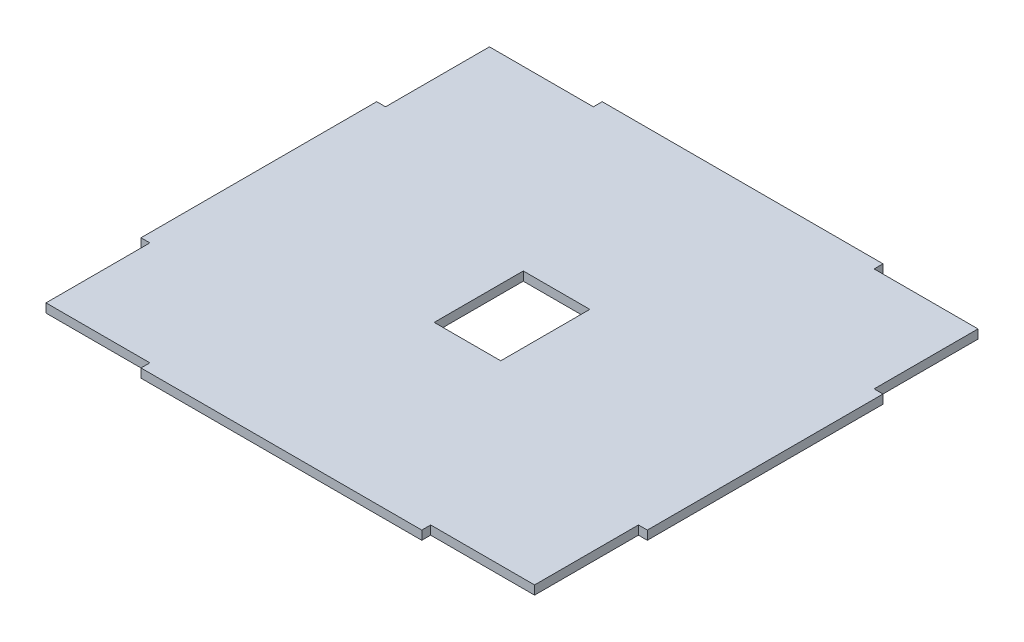
SolidWorks part; units mm, degrees
ref_plane "Front Plane" through (0, 0, 0) normal (0, 0, 1) x (1, 0, 0)
ref_plane "Top Plane" through (0, 0, 0) normal (0, 1, 0) x (1, 0, 0)
ref_plane "Right Plane" through (0, 0, 0) normal (1, 0, 0) x (0, 0, -1)
sketch "Sketch1" plane through (0, 0, 0) normal (0, 1, 0) x (1, 0, 0)
  line L0 (-55.023, 49.943) -> (-31.623, 49.943)
  line L1 (-31.623, -51.943) -> (31.623, -51.943)
  line L2 (-57.023, -26.543) -> (-57.023, 26.543)
  line L3 (-31.623, 51.943) -> (31.623, 51.943)
  line L4 (57.023, -26.543) -> (57.023, 26.543)
  line L5 (31.623, -49.943) -> (55.023, -49.943)
  line L6 (-57.023, -51.943) -> (-57.023, 51.943) construction
  line L7 (55.023, -49.943) -> (55.023, -26.543)
  line L8 (-55.023, -49.943) -> (-31.623, -49.943)
  line L9 (-55.023, -49.943) -> (-55.023, -26.543)
  line L10 (-31.623, 51.943) -> (-31.623, 49.943)
  line L11 (31.623, 51.943) -> (31.623, 49.943)
  line L12 (-57.023, 26.543) -> (-55.023, 26.543)
  line L13 (-57.023, -26.543) -> (-55.023, -26.543)
  line L14 (-31.623, 28.8058) -> (-31.623, 26.543)
  line L15 (-31.623, 28.8058) -> (-29.1389, 26.543) construction
  line L16 (-31.623, 26.543) -> (-29.1389, 26.543)
  line L17 (-31.623, -26.543) -> (-31.623, -28.8058)
  line L18 (57.023, -51.943) -> (57.023, 51.943) construction
  line L19 (-57.023, -51.943) -> (57.023, -51.943) construction
  line L20 (31.623, -26.543) -> (31.623, -28.8058)
  line L21 (55.023, 26.543) -> (57.023, 26.543)
  line L22 (55.023, -26.543) -> (57.023, -26.543)
  line L23 (0, 51.943) -> (0, -50.798) construction
  line L24 (31.623, -49.943) -> (31.623, -51.943)
  line L25 (-31.623, -26.543) -> (-29.1389, -26.543)
  line L26 (-31.623, -28.8058) -> (-29.1389, -26.543) construction
  line L27 (-31.623, -49.943) -> (-31.623, -51.943)
  line L28 (-57.023, 51.943) -> (57.023, 51.943) construction
  line L29 (-55.023, -49.943) -> (55.023, -49.943) construction
  line L30 (55.023, 26.543) -> (55.023, 49.943)
  line L31 (55.023, -49.943) -> (55.023, 49.943) construction
  line L32 (-55.023, 26.543) -> (-55.023, 49.943)
  line L33 (-55.023, -49.943) -> (-55.023, 49.943) construction
  line L34 (31.623, 49.943) -> (55.023, 49.943)
  line L35 (-55.023, 49.943) -> (55.023, 49.943) construction
  line L36 (-57.023, 0) -> (57.023, 0) construction
  line L39 (-7.493, -10.033) -> (7.493, -10.033)
  line L40 (-7.493, -10.033) -> (-7.493, 10.033)
  line L41 (-7.493, 10.033) -> (7.493, 10.033)
  line L42 (7.493, -10.033) -> (7.493, 10.033)
  line L43 (-7.493, -10.033) -> (7.493, 10.033) construction
  line L44 (-7.493, 10.033) -> (7.493, -10.033) construction
  point P0 (0, 0)
  point P36 (0, 0)
  dimension "D4" = 25.4
  dimension "D1" = 14.986
  dimension "D2" = 20.066
  dimension "D5" = 25.4
  dimension "D6" = 25.4
  dimension "D7" = 25.4
  dimension "D3" = 2
extrude "Boss-Extrude1" add sketch "Sketch1" along normal blind 2
